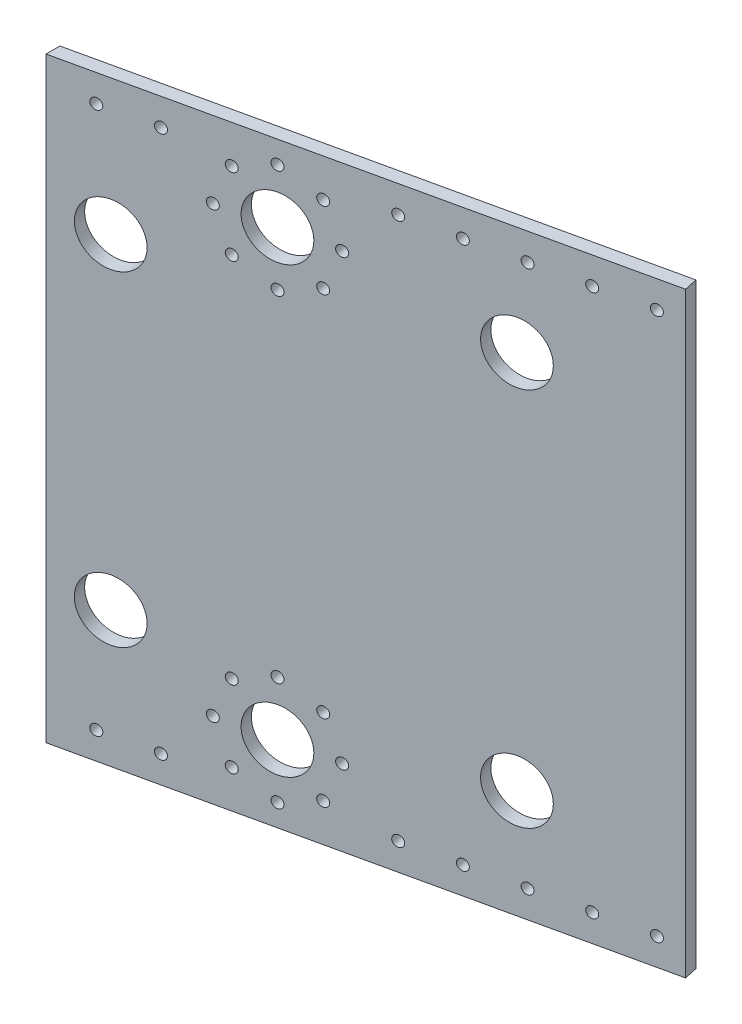
SolidWorks part; units mm, degrees
ref_plane "Front Plane" through (0, 0, 0) normal (0, 0, 1) x (1, 0, 0)
ref_plane "Top Plane" through (0, 0, 0) normal (0, 1, 0) x (1, 0, 0)
ref_plane "Right Plane" through (0, 0, 0) normal (1, 0, 0) x (0, 0, -1)
ref_plane "Plane1" through (158.2688, 0, 713.9043) normal (0.2164, 0, 0.9763) x (0, 1, 0)
sketch "Sketch1" plane through (158.2688, 0, 713.9043) normal (0.2164, 0, 0.9763) x (0, 1, 0)
  line L0 (284.48, -574.4213) -> (284.48, -323.2301)
  line L1 (284.48, -323.2301) -> (6.35, -323.2301)
  line L2 (6.35, -323.2301) -> (6.35, -574.4213)
  line L3 (6.35, -574.4213) -> (284.48, -574.4213)
extrude "Boss-Extrude1" add sketch "Sketch1" against normal blind 6.35
draft "Draft1" type of draft neutral plane draft angle 12.5 faces to draft 1 face at (473.1498, 145.415, 640.8448) neutral plane through (158.2688, 0, 713.9043) neutral plane normal (0.2164, 0, 0.9763) reverse direction yes parameters "D1"=12.5
hole_wizard "Hole1" positions "Sketch3" profile "Sketch2" legacy
sketch "Sketch3" plane through (158.2688, 0, 713.9043) normal (0.2164, 0, 0.9763) x (0.9763, 0, -0.2164)
  point P0 (348.6301, 69.85)
  point P1 (508.1661, 57.15)
  point P2 (508.1661, 234.95)
  point P3 (348.6301, 222.25)
  point P4 (414.1127, 42.0996)
  point P5 (414.1127, 250.0004)
sketch "Sketch2" plane through (498.6349, 69.85, 638.447) normal (0, 1, 0) x (0.9763, 0, -0.2164)
  line L0 (0, 0) -> (0, 59.1315)
  line L1 (0, 59.1315) -> (14.2875, 59.1315)
  line L2 (14.2875, 59.1315) -> (14.2875, 0)
  line L3 (14.2875, 0) -> (0, 0)
  line L4 (0, 110) -> (0, -10) construction
  dimension "Diameter" = 28.575
  dimension "Depth" = 59.1315
hole_wizard "#7 (0.201) Diameter Hole1" positions "Sketch5" profile "Sketch4" hole size "#7" standard "ANSI Inch"
sketch "Sketch5" plane through (158.2688, 0, 713.9043) normal (0.2164, 0, 0.9763) x (0.9763, 0, -0.2164)
  line L0 (563.1291, 273.05) -> (537.7291, 273.05) construction
  line L1 (537.7291, 273.05) -> (512.3291, 273.05) construction
  line L2 (512.3291, 273.05) -> (486.9291, 273.05) construction
  line L3 (486.9291, 273.05) -> (461.5291, 273.05) construction
  line L5 (342.9689, 273.05) -> (368.3689, 273.05) construction
  line L7 (342.9689, 273.05) -> (323.2301, 273.05) construction
  line L8 (323.2301, 284.48) -> (323.2301, 6.35) construction
  line L10 (574.4213, 284.48) -> (323.2301, 284.48) construction
  point P0 (461.5291, 273.05)
  point P1 (512.3291, 273.05)
  point P2 (563.1291, 273.05)
  point P3 (537.7291, 273.05)
  point P4 (486.9291, 273.05)
  point P5 (368.3689, 273.05)
  point P6 (461.5291, 19.05)
  point P7 (486.9291, 19.05)
  point P8 (512.3291, 19.05)
  point P9 (537.7291, 19.05)
  point P10 (563.1291, 19.05)
  point P11 (368.3689, 19.05)
  point P12 (342.9689, 19.05)
  point P13 (432.0732, 24.1391)
  point P14 (432.0732, 60.0601)
  point P15 (396.1521, 24.1391)
  point P16 (396.1521, 60.0601)
  point P17 (432.0732, 267.9609)
  point P18 (396.1521, 267.9609)
  point P19 (432.0732, 232.0399)
  point P20 (396.1521, 232.0399)
  point P21 (342.9689, 273.05)
  dimension "D1" = 19.7388
  dimension "D2" = 25.4
  dimension "D3" = 11.43
  dimension "D4" = 93.1602
sketch "Sketch4" plane through (608.8578, 273.05, 614.0111) normal (0, 1, 0) x (0.9763, 0, -0.2164)
  line L0 (0, 0) -> (0, 59.1315)
  line L1 (0, 59.1315) -> (2.5527, 59.1315)
  line L2 (2.5527, 59.1315) -> (2.5527, 0)
  line L5 (2.5527, 0) -> (0, 0)
  line L11 (0, -6.35) -> (0, 107.95) construction
  dimension "Thru Hole Dia." = 5.1054
  dimension "Thru Hole Depth" = 59.1315
sketch "Sketch6" plane through (158.2688, 0, 713.9043) normal (0.2164, 0, 0.9763) x (0.9763, 0, -0.2164)
  line L0 (414.1127, 250.0004) -> (388.7127, 250.0004) construction
  line L1 (414.1127, 42.0996) -> (388.7127, 42.0996) construction
  circle A0 centre (388.7127, 250.0004) radius 2.5527
  circle A1 centre (414.1127, 275.4004) radius 2.5527
  circle A2 centre (439.5127, 250.0004) radius 2.5527
  circle A3 centre (414.1127, 224.6004) radius 2.5527
  circle A4 centre (388.7127, 42.0996) radius 2.5527
  circle A5 centre (414.1127, 67.4996) radius 2.5527
  circle A6 centre (439.5127, 42.0996) radius 2.5527
  circle A7 centre (414.1127, 16.6996) radius 2.5527
  dimension "D2" = 5.1054
  dimension "D4" = 5.1054
  dimension "D1" = 25.4
  dimension "D3" = 4
  dimension "D5" = 4
extrude "Cut-Extrude1" cut sketch "Sketch6" against normal through all both and the other way through all
sketch "Sketch7" plane through (0, 284.48, 0) normal (0, 1, 0) x (1, 0, 0)
  line L15 (473.837, -637.4403) -> (473.837, -643.9445)
  line L16 (473.837, -643.9445) -> (719.074, -589.5768)
  line L17 (719.074, -589.5768) -> (717.6996, -583.3773)
  line L18 (717.6996, -583.3773) -> (473.837, -637.4403)
  line L19 (473.837, -637.4403) -> (473.837, -643.9445)
  line L20 (473.837, -643.9445) -> (719.074, -589.5768)
  line L21 (719.074, -589.5768) -> (717.6996, -583.3773)
  line L22 (717.6996, -583.3773) -> (473.837, -637.4403)
  dimension "D1" = 0
extrude "Boss-Extrude2" add sketch "Sketch7" along normal blind 1.27
